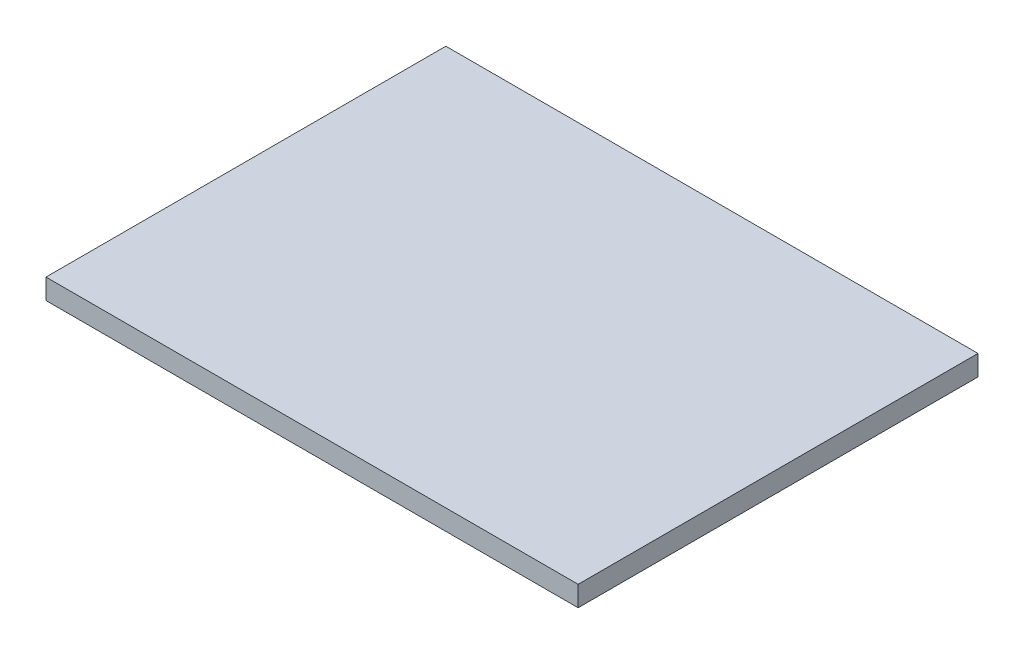
SolidWorks part; units mm, degrees
ref_plane "Front Plane" through (0, 0, 0) normal (0, 0, 1) x (1, 0, 0)
ref_plane "Top Plane" through (0, 0, 0) normal (0, 1, 0) x (1, 0, 0)
ref_plane "Right Plane" through (0, 0, 0) normal (1, 0, 0) x (0, 0, -1)
sketch "Sketch3" plane through (0, 0, 0) normal (0, 1, 0) x (1, 0, 0)
  line L1 (0, 0) -> (2615, 0)
  line L2 (0, 0) -> (0, 1965)
  line L3 (0, 1965) -> (2615, 1965)
  line L4 (2615, 0) -> (2615, 1965)
  dimension "D1" = 2615
  dimension "D2" = 1965
extrude "Boss-Extrude1" add sketch "Sketch3" along normal blind 100
